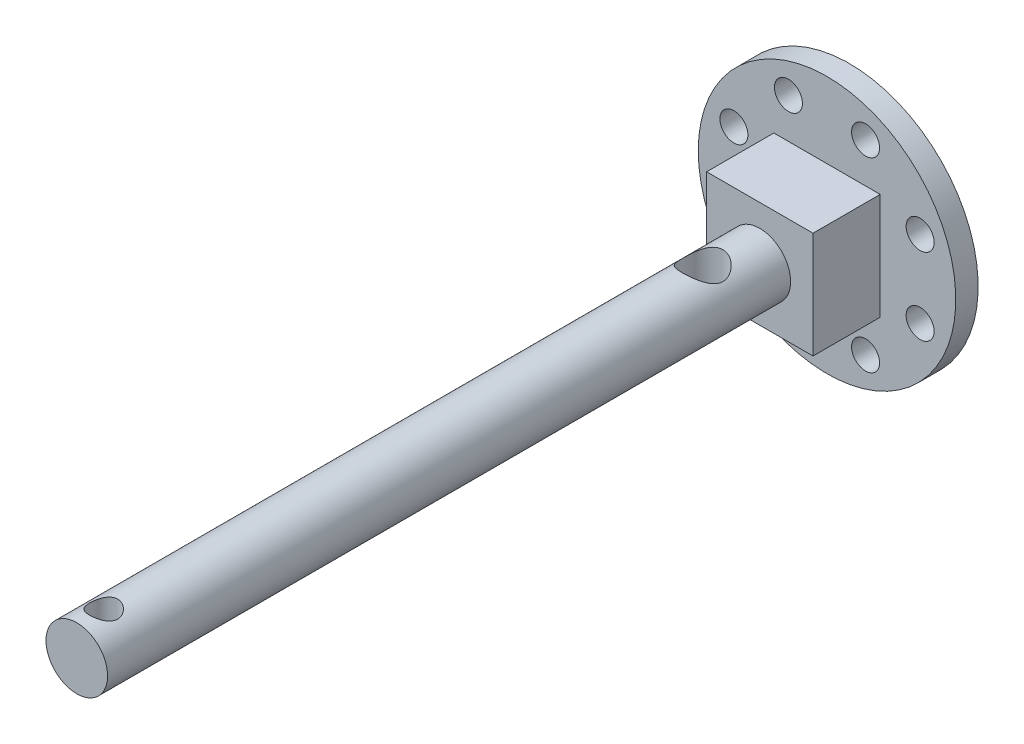
SolidWorks part; units mm, degrees
ref_plane "정면" through (0, 0, 0) normal (0, 0, 1) x (1, 0, 0)
ref_plane "윗면" through (0, 0, 0) normal (0, 1, 0) x (1, 0, 0)
ref_plane "우측면" through (0, 0, 0) normal (1, 0, 0) x (0, 0, -1)
sketch "스케치1" plane through (0, 0, 0) normal (0, 0, 1) x (1, 0, 0)
  circle A0 centre (0, 0) radius 2.75
  dimension "D1" = 5.5
extrude "보스-돌출1" add sketch "스케치1" along normal blind 1 contours A0
sketch "스케치3" plane through (0, 0, 0) normal (0, 0, -1) x (-1, 0, 0)
  line L1 (4.75, -4.75) -> (-4.75, -4.75)
  line L2 (4.75, -4.75) -> (4.75, 4.75)
  line L3 (4.75, 4.75) -> (-4.75, 4.75)
  line L4 (-4.75, -4.75) -> (-4.75, 4.75)
  line L5 (4.75, -4.75) -> (-4.75, 4.75) construction
  line L6 (4.75, 4.75) -> (-4.75, -4.75) construction
  point P0 (0, 0)
  dimension "D1" = 9.5
  dimension "D2" = 9.5
extrude "보스-돌출2" add sketch "스케치3" along normal blind 6
sketch "스케치11" plane through (0, 4.75, 0) normal (0, 1, 0) x (1, 0, 0)
  line L2 (-4.75, 6) -> (-4.75, 0) construction
  line L4 (-4.75, 2.6468) -> (4.75, 2.6468) construction
  line L5 (4.75, 6) -> (4.75, 0) construction
sketch "스케치12" plane through (0, 0, 1) normal (0, 0, 1) x (1, 0, 0)
  line L0 (-4.75, 4.75) -> (4.75, 4.75) construction
  line L1 (4.75, -4.75) -> (-4.75, -4.75)
  line L2 (4.75, -4.75) -> (4.75, 4.75)
  line L3 (4.75, 4.75) -> (-4.75, 4.75)
  line L4 (-4.75, -4.75) -> (-4.75, 4.75)
  line L5 (4.75, -4.75) -> (-4.75, 4.75) construction
  line L6 (4.75, 4.75) -> (-4.75, -4.75) construction
  line L7 (-4.75, -4.75) -> (-4.75, 4.75) construction
  point P0 (0, 0)
extrude "보스-돌출5" add sketch "스케치12" along normal blind 45
sketch "스케치15" plane through (0, 0, 46) normal (0, 0, 1) x (1, 0, 0)
  line L1 (2.95, -10.0246) -> (-2.95, -10.0246)
  line L2 (2.95, -10.0246) -> (2.95, 10.0246)
  line L3 (2.95, 10.0246) -> (-2.95, 10.0246)
  line L4 (-2.95, -10.0246) -> (-2.95, 10.0246)
  line L5 (2.95, -10.0246) -> (-2.95, 10.0246) construction
  line L6 (2.95, 10.0246) -> (-2.95, -10.0246) construction
  point P0 (0, 0)
  dimension "D1" = 5.9
extrude "보스-돌출6" add sketch "스케치15" along normal blind 6
sketch "스케치16" plane through (0, 4.75, 0) normal (0, 1, 0) x (1, 0, 0)
  line L0 (4.75, -1) -> (-4.75, -1) construction
  circle A0 centre (0, -3) radius 1.25
  dimension "D2" = 2.5
  dimension "D1" = 2
sketch "스케치17" plane through (0, 4.75, 0) normal (0, 1, 0) x (1, 0, 0)
  line L0 (-4.75, 0) -> (4.75, 0) construction
  circle A0 centre (0, -5.1) radius 1.8
  dimension "D2" = 3.6
  dimension "D1" = 5.1
extrude "컷-돌출9" cut sketch "스케치17" against normal blind 5
sketch "스케치18" plane through (0, 0, 1) normal (0, 0, -1) x (-1, 0, 0)
  circle A0 centre (0, 0) radius 2.75
  dimension "D1" = 5.5
extrude "컷-돌출10" cut sketch "스케치18" against normal blind 60 flip side to cut
sketch "스케치19" plane through (0, 0, -6) normal (0, 0, -1) x (-1, 0, 0)
  circle A0 centre (0, 0) radius 11.5
  dimension "D1" = 23
extrude "보스-돌출7" add sketch "스케치19" along normal blind 2
sketch "스케치20" plane through (0, 0, -6) normal (0, 0, 1) x (1, 0, 0)
  line L0 (0, 0) -> (0, 13.7517) construction
  line L1 (0, 0) -> (3.4442, 8.3149) construction
  circle A0 centre (3.4442, 8.3149) radius 1.25
  circle A1 centre (8.3149, 3.4442) radius 1.25
  circle A2 centre (8.3149, -3.4442) radius 1.25
  circle A3 centre (3.4442, -8.3149) radius 1.25
  circle A4 centre (-3.4442, -8.3149) radius 1.25
  circle A5 centre (-8.3149, -3.4442) radius 1.25
  circle A6 centre (-8.3149, 3.4442) radius 1.25
  circle A7 centre (-3.4442, 8.3149) radius 1.25
  point P24 (0, 0)
  dimension "D2" = 9
  dimension "D3" = 22.5
  dimension "D1" = 2.5
  dimension "D4" = 8
extrude "컷-돌출11" cut sketch "스케치20" against normal blind 2
sketch "스케치21" plane through (0, 0, -8) normal (0, 0, -1) x (-1, 0, 0)
  circle A0 centre (0, 0) radius 4.5
  dimension "D1" = 9
extrude "컷-돌출13" cut sketch "스케치21" against normal blind 5.4
sketch "스케치22" plane through (0, 0, 52) normal (0, 0, 1) x (1, 0, 0)
  circle A0 centre (0, 0) radius 2.75
  dimension "D1" = 5.5
extrude "보스-돌출8" add sketch "스케치22" along normal blind 12
ref_plane "평면1" through (0, 2.75, 0) normal (0, 1, 0) x (1, 0, 0)
sketch "스케치23" plane through (0, 2.75, 0) normal (0, 1, 0) x (1, 0, 0)
  circle A0 centre (0, -90) radius 1.25
  dimension "D1" = 2.5
  dimension "D2" = 90
sketch "스케치24" plane through (0, 0, 64) normal (0, 0, 1) x (1, 0, 0)
  circle A0 centre (0, 0) radius 2.75
extrude "컷-돌출15" cut sketch "스케치24" against normal blind 3
sketch "스케치25" plane through (0, 2.75, 0) normal (0, 1, 0) x (1, 0, 0)
  line L0 (-2.75, -61) -> (2.75, -61) construction
  circle A0 centre (0, -58.6) radius 1.25
  dimension "D1" = 2.5
  dimension "D2" = 2.4
extrude "컷-돌출16" cut sketch "스케치25" against normal blind 9
